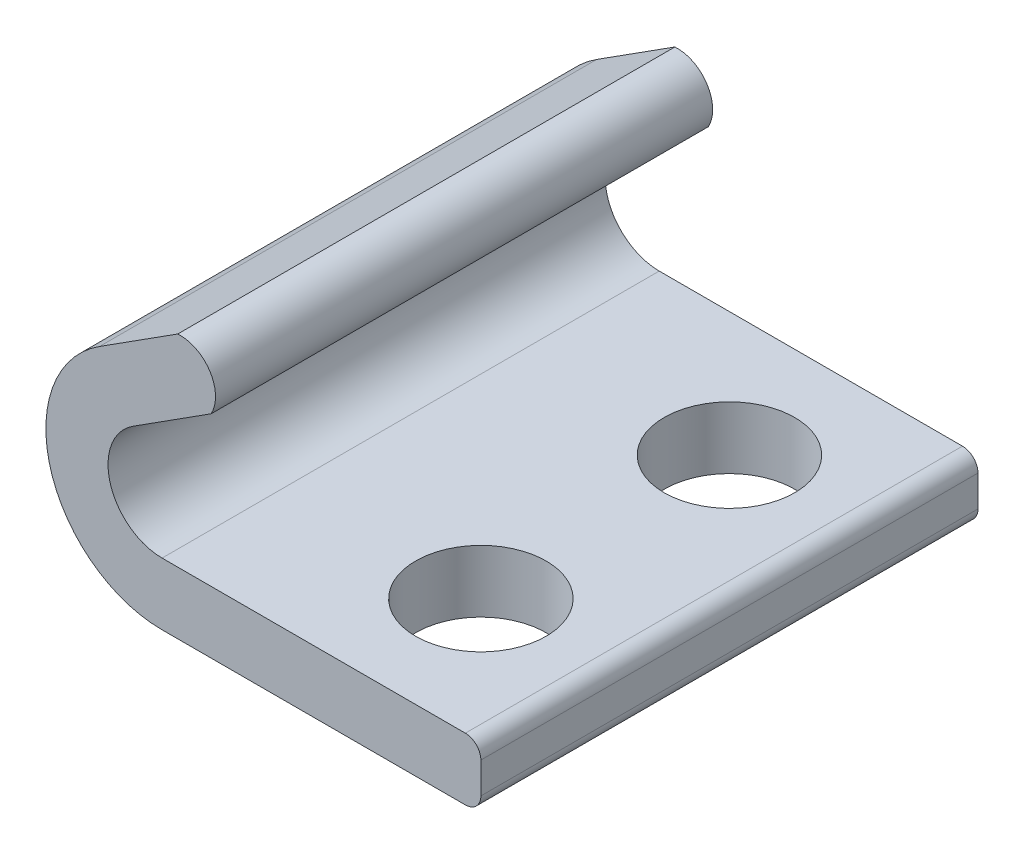
SolidWorks part; units mm, degrees
ref_plane "Спереди" through (0, 0, 0) normal (0, 0, 1) x (1, 0, 0)
ref_plane "Сверху" through (0, 0, 0) normal (0, 1, 0) x (1, 0, 0)
ref_plane "Справа" through (0, 0, 0) normal (1, 0, 0) x (0, 0, -1)
ref_plane "Плоскость1" through (0, 0, 8) normal (0, 0, 1) x (1, 0, 0)
sketch "Эскиз1" plane through (0, 0, 8) normal (0, 0, 1) x (1, 0, 0)
  line L0 (-9.7563, 8.4974) -> (-12.2714, 6.8931)
  line L1 (-10.26, 0) -> (0, 0)
  line L2 (0, 0) -> (0, 2)
  line L3 (0, 2) -> (-10.26, 2)
  line L4 (-11.1958, 5.2069) -> (-8.6807, 6.8113)
  arc A0 (-12.2714, 6.8931) -> (-10.26, 0) centre (-10.26, 3.74) ccw
  arc A1 (-10.26, 2) -> (-11.1958, 5.2069) centre (-10.26, 3.74) cw
  arc A2 (-8.6807, 6.8113) -> (-9.7563, 8.4974) centre (-9.68, 7.36) ccw
extrude "Бобышка-Вытянуть1" add sketch "Эскиз1" against normal blind 16
hole_wizard "Диаметр отверстия Ø4.2 (4.2)1" positions "Эскиз3" profile "Эскиз2" hole size "Ø4.2" standard "Ansi Metric"
sketch "Эскиз3" plane through (0, 2, 0) normal (0, 1, 0) x (1, 0, 0)
  point P0 (-4, 4)
  point P1 (-4, -4)
sketch "Эскиз2" plane through (-4, 2, -4) normal (1, 0, 0) x (0, 0, 1)
  line L0 (0, 0) -> (0, 2)
  line L1 (0, 2) -> (2.1, 2)
  line L2 (2.1, 2) -> (2.1, 0)
  line L5 (2.1, 0) -> (0, 0)
  line L11 (0, -6.35) -> (0, 107.95) construction
  dimension "Диаметр сквозного отверстия" = 4.2
  dimension "Глубина сквозного отверстия" = 2
fillet "Скругление1" radius 0.5 2 edges at (0, 2, 0) (0, 0, 0)
